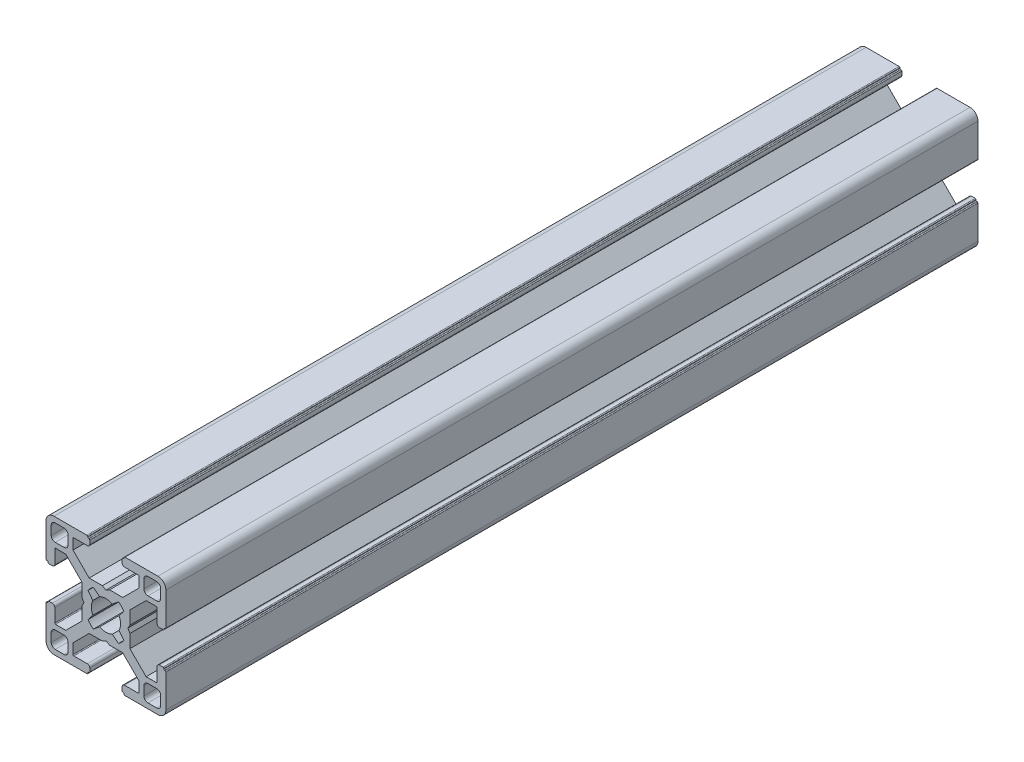
SolidWorks part; units mm, degrees
material "6061 Alloy"
ref_plane "Front" through (0, 0, 0) normal (0, 0, 1) x (1, 0, 0)
ref_plane "Top" through (0, 0, 0) normal (0, 1, 0) x (1, 0, 0)
ref_plane "Right" through (0, 0, 0) normal (1, 0, 0) x (0, 0, -1)
sketch "Sketch1" plane through (0, 0, 0) normal (0, 0, 1) x (1, 0, 0)
  line L0 (13.7, 12.7) -> (13.7, 10.5)
  line L1 (10.5, 9.5) -> (12.7, 9.5)
  line L2 (9.5, 12.7) -> (9.5, 10.5)
  line L3 (10.5, 13.7) -> (12.7, 13.7)
  line L4 (3.1359, 4.5184) -> (1.6001, 3.2806)
  line L5 (3.2806, 1.6001) -> (4.5053, 3.1547)
  line L6 (6.0045, 0.9) -> (5.4849, 0)
  line L7 (6.0045, 4.2045) -> (6.0045, 0.9)
  line L8 (0, -5.4849) -> (0.9, -6)
  line L9 (0.9, -6) -> (4.2045, -6)
  line L10 (4.2045, -6) -> (8.25, -10.05)
  line L11 (8.25, -10.05) -> (8.25, -12.6)
  line L12 (4.65, -12.8) -> (8.05, -12.8)
  line L13 (4.05, -14.3) -> (4.05, -13.4)
  line L14 (4.25, -14.5) -> (4.35, -14.5)
  line L15 (4.55, -14.8) -> (4.55, -14.7)
  line L16 (4.75, -15) -> (13, -15)
  line L17 (15, -13) -> (15, -4.75)
  line L18 (14.7, -4.55) -> (14.8, -4.55)
  line L19 (14.5, -4.35) -> (14.5, -4.25)
  line L20 (13.4, -4.05) -> (14.3, -4.05)
  line L21 (12.8, -8.05) -> (12.8, -4.65)
  line L22 (12.6, -8.25) -> (10.05, -8.25)
  line L23 (10.05, -8.25) -> (6.0045, -4.2045)
  line L24 (6.0045, -4.2045) -> (6.0045, -0.9)
  line L25 (6.0045, -0.9) -> (5.4849, 0)
  line L26 (10.05, 8.25) -> (6.0045, 4.2045)
  line L27 (12.6, 8.25) -> (10.05, 8.25)
  line L28 (12.8, 8.05) -> (12.8, 4.65)
  line L29 (13.4, 4.05) -> (14.3, 4.05)
  line L30 (14.5, 4.35) -> (14.5, 4.25)
  line L31 (14.7, 4.55) -> (14.8, 4.55)
  line L32 (15, 13) -> (15, 4.75)
  line L33 (4.75, 15) -> (13, 15)
  line L34 (4.55, 14.8) -> (4.55, 14.7)
  line L35 (4.25, 14.5) -> (4.35, 14.5)
  line L36 (4.05, 14.3) -> (4.05, 13.4)
  line L37 (4.65, 12.8) -> (8.05, 12.8)
  line L38 (8.25, 10.05) -> (8.25, 12.6)
  line L39 (4.2045, 6) -> (8.25, 10.05)
  line L40 (0.9, 6) -> (4.2045, 6)
  line L41 (0, 5.4849) -> (0.9, 6)
  line L42 (-13.7, -12.7) -> (-13.7, -10.5)
  line L43 (-10.5, -9.5) -> (-12.7, -9.5)
  line L44 (-9.5, -12.7) -> (-9.5, -10.5)
  line L45 (-10.5, -13.7) -> (-12.7, -13.7)
  line L46 (-3.1359, -4.5184) -> (-1.6001, -3.2806)
  line L47 (-3.2806, -1.6001) -> (-4.5053, -3.1547)
  line L48 (0, 5.4849) -> (-0.9, 6)
  line L49 (-0.9, 6) -> (-4.2045, 6)
  line L50 (-4.2045, 6) -> (-8.25, 10.05)
  line L51 (-8.25, 10.05) -> (-8.25, 12.6)
  line L52 (-4.65, 12.8) -> (-8.05, 12.8)
  line L53 (-4.05, 14.3) -> (-4.05, 13.4)
  line L54 (-4.25, 14.5) -> (-4.35, 14.5)
  line L55 (-4.55, 14.8) -> (-4.55, 14.7)
  line L56 (-4.75, 15) -> (-13, 15)
  line L57 (-15, 13) -> (-15, 4.75)
  line L58 (-14.7, 4.55) -> (-14.8, 4.55)
  line L59 (-14.5, 4.35) -> (-14.5, 4.25)
  line L60 (-13.4, 4.05) -> (-14.3, 4.05)
  line L61 (-12.8, 8.05) -> (-12.8, 4.65)
  line L62 (-12.6, 8.25) -> (-10.05, 8.25)
  line L63 (-10.05, 8.25) -> (-6.0045, 4.2045)
  line L64 (-6.0045, -0.9) -> (-5.4849, 0)
  line L65 (-6.0045, -4.2045) -> (-6.0045, -0.9)
  line L66 (-10.05, -8.25) -> (-6.0045, -4.2045)
  line L67 (-12.6, -8.25) -> (-10.05, -8.25)
  line L68 (-12.8, -8.05) -> (-12.8, -4.65)
  line L69 (-13.4, -4.05) -> (-14.3, -4.05)
  line L70 (-14.5, -4.35) -> (-14.5, -4.25)
  line L71 (-14.7, -4.55) -> (-14.8, -4.55)
  line L72 (-15, -13) -> (-15, -4.75)
  line L73 (-4.75, -15) -> (-13, -15)
  line L74 (-4.55, -14.8) -> (-4.55, -14.7)
  line L75 (-4.25, -14.5) -> (-4.35, -14.5)
  line L76 (-4.05, -14.3) -> (-4.05, -13.4)
  line L77 (3.2806, -1.6001) -> (4.5053, -3.1547)
  line L78 (3.1359, -4.5184) -> (1.6001, -3.2806)
  line L79 (-4.65, -12.8) -> (-8.05, -12.8)
  line L80 (-8.25, -10.05) -> (-8.25, -12.6)
  line L81 (-4.2045, -6) -> (-8.25, -10.05)
  line L82 (-0.9, -6) -> (-4.2045, -6)
  line L83 (0, -5.4849) -> (-0.9, -6)
  line L84 (10.5, -13.7) -> (12.7, -13.7)
  line L85 (9.5, -12.7) -> (9.5, -10.5)
  line L86 (10.5, -9.5) -> (12.7, -9.5)
  line L87 (13.7, -12.7) -> (13.7, -10.5)
  line L88 (-6.0045, 4.2045) -> (-6.0045, 0.9)
  line L89 (-6.0045, 0.9) -> (-5.4849, 0)
  line L90 (-3.2806, 1.6001) -> (-4.5053, 3.1547)
  line L91 (-3.1359, 4.5184) -> (-1.6001, 3.2806)
  line L92 (-10.5, 13.7) -> (-12.7, 13.7)
  line L93 (-9.5, 12.7) -> (-9.5, 10.5)
  line L94 (-10.5, 9.5) -> (-12.7, 9.5)
  line L95 (-13.7, 12.7) -> (-13.7, 10.5)
  line L96 (-23.4857, 0) -> (20.9308, 0) construction
  line L97 (0, 17.9563) -> (0, -17.361) construction
  arc A0 (13.7, 12.7) -> (12.7, 13.7) centre (12.7, 12.7) ccw
  arc A1 (12.7, 9.5) -> (13.7, 10.5) centre (12.7, 10.5) ccw
  arc A2 (9.5, 10.5) -> (10.5, 9.5) centre (10.5, 10.5) ccw
  arc A3 (10.5, 13.7) -> (9.5, 12.7) centre (10.5, 12.7) ccw
  arc A4 (1.6001, 3.2806) -> (-1.6001, 3.2806) centre (0, 0) ccw
  arc A5 (8.25, -12.6) -> (8.05, -12.8) centre (8.05, -12.6) cw
  arc A6 (4.65, -12.8) -> (4.05, -13.4) centre (4.65, -13.4) ccw
  arc A7 (4.05, -14.3) -> (4.25, -14.5) centre (4.25, -14.3) ccw
  arc A8 (4.35, -14.5) -> (4.55, -14.7) centre (4.35, -14.7) cw
  arc A9 (4.55, -14.8) -> (4.75, -15) centre (4.75, -14.8) ccw
  arc A10 (13, -15) -> (15, -13) centre (13, -13) ccw
  arc A11 (15, -4.75) -> (14.8, -4.55) centre (14.8, -4.75) ccw
  arc A12 (14.7, -4.55) -> (14.5, -4.35) centre (14.7, -4.35) cw
  arc A13 (14.5, -4.25) -> (14.3, -4.05) centre (14.3, -4.25) ccw
  arc A14 (13.4, -4.05) -> (12.8, -4.65) centre (13.4, -4.65) ccw
  arc A15 (12.8, -8.05) -> (12.6, -8.25) centre (12.6, -8.05) cw
  arc A16 (4.5053, 3.1547) -> (3.1359, 4.5184) centre (0, 0) ccw
  arc A17 (12.8, 8.05) -> (12.6, 8.25) centre (12.6, 8.05) ccw
  arc A18 (13.4, 4.05) -> (12.8, 4.65) centre (13.4, 4.65) cw
  arc A19 (14.5, 4.25) -> (14.3, 4.05) centre (14.3, 4.25) cw
  arc A20 (14.7, 4.55) -> (14.5, 4.35) centre (14.7, 4.35) ccw
  arc A21 (15, 4.75) -> (14.8, 4.55) centre (14.8, 4.75) cw
  arc A22 (13, 15) -> (15, 13) centre (13, 13) cw
  arc A23 (4.55, 14.8) -> (4.75, 15) centre (4.75, 14.8) cw
  arc A24 (4.35, 14.5) -> (4.55, 14.7) centre (4.35, 14.7) ccw
  arc A25 (4.05, 14.3) -> (4.25, 14.5) centre (4.25, 14.3) cw
  arc A26 (4.65, 12.8) -> (4.05, 13.4) centre (4.65, 13.4) cw
  arc A27 (8.25, 12.6) -> (8.05, 12.8) centre (8.05, 12.6) ccw
  arc A28 (-13.7, -12.7) -> (-12.7, -13.7) centre (-12.7, -12.7) ccw
  arc A29 (-12.7, -9.5) -> (-13.7, -10.5) centre (-12.7, -10.5) ccw
  arc A30 (-9.5, -10.5) -> (-10.5, -9.5) centre (-10.5, -10.5) ccw
  arc A31 (-10.5, -13.7) -> (-9.5, -12.7) centre (-10.5, -12.7) ccw
  arc A32 (-4.5053, -3.1547) -> (-3.1359, -4.5184) centre (0, 0) ccw
  arc A33 (-3.2806, 1.6001) -> (-3.2806, -1.6001) centre (0, 0) ccw
  arc A34 (-8.25, 12.6) -> (-8.05, 12.8) centre (-8.05, 12.6) cw
  arc A35 (-4.65, 12.8) -> (-4.05, 13.4) centre (-4.65, 13.4) ccw
  arc A36 (-4.05, 14.3) -> (-4.25, 14.5) centre (-4.25, 14.3) ccw
  arc A37 (-4.35, 14.5) -> (-4.55, 14.7) centre (-4.35, 14.7) cw
  arc A38 (-4.55, 14.8) -> (-4.75, 15) centre (-4.75, 14.8) ccw
  arc A39 (-13, 15) -> (-15, 13) centre (-13, 13) ccw
  arc A40 (-15, 4.75) -> (-14.8, 4.55) centre (-14.8, 4.75) ccw
  arc A41 (-14.7, 4.55) -> (-14.5, 4.35) centre (-14.7, 4.35) cw
  arc A42 (-14.5, 4.25) -> (-14.3, 4.05) centre (-14.3, 4.25) ccw
  arc A43 (-13.4, 4.05) -> (-12.8, 4.65) centre (-13.4, 4.65) ccw
  arc A44 (-12.8, 8.05) -> (-12.6, 8.25) centre (-12.6, 8.05) cw
  arc A45 (-4.5053, 3.1547) -> (-3.1359, 4.5184) centre (0, 0) cw
  arc A46 (-12.8, -8.05) -> (-12.6, -8.25) centre (-12.6, -8.05) ccw
  arc A47 (-13.4, -4.05) -> (-12.8, -4.65) centre (-13.4, -4.65) cw
  arc A48 (-14.5, -4.25) -> (-14.3, -4.05) centre (-14.3, -4.25) cw
  arc A49 (3.2806, 1.6001) -> (3.2806, -1.6001) centre (0, 0) cw
  arc A50 (4.5053, -3.1547) -> (3.1359, -4.5184) centre (0, 0) cw
  arc A51 (1.6001, -3.2806) -> (-1.6001, -3.2806) centre (0, 0) cw
  arc A52 (-14.7, -4.55) -> (-14.5, -4.35) centre (-14.7, -4.35) ccw
  arc A53 (-15, -4.75) -> (-14.8, -4.55) centre (-14.8, -4.75) cw
  arc A54 (-13, -15) -> (-15, -13) centre (-13, -13) cw
  arc A55 (-4.55, -14.8) -> (-4.75, -15) centre (-4.75, -14.8) cw
  arc A56 (10.5, -13.7) -> (9.5, -12.7) centre (10.5, -12.7) cw
  arc A57 (9.5, -10.5) -> (10.5, -9.5) centre (10.5, -10.5) cw
  arc A58 (12.7, -9.5) -> (13.7, -10.5) centre (12.7, -10.5) cw
  arc A59 (13.7, -12.7) -> (12.7, -13.7) centre (12.7, -12.7) cw
  arc A60 (-4.35, -14.5) -> (-4.55, -14.7) centre (-4.35, -14.7) ccw
  arc A61 (-4.05, -14.3) -> (-4.25, -14.5) centre (-4.25, -14.3) cw
  arc A62 (-4.65, -12.8) -> (-4.05, -13.4) centre (-4.65, -13.4) cw
  arc A63 (-8.25, -12.6) -> (-8.05, -12.8) centre (-8.05, -12.6) ccw
  arc A64 (-10.5, 13.7) -> (-9.5, 12.7) centre (-10.5, 12.7) cw
  arc A65 (-9.5, 10.5) -> (-10.5, 9.5) centre (-10.5, 10.5) cw
  arc A66 (-12.7, 9.5) -> (-13.7, 10.5) centre (-12.7, 10.5) cw
  arc A67 (-13.7, 12.7) -> (-12.7, 13.7) centre (-12.7, 12.7) cw
  point P81 (15, 15)
  point P82 (0, 15)
  point P203 (0, -15)
  point P204 (15, -15)
  point P206 (0, 0)
  point P207 (15, 0)
  point P219 (-15, 0)
  point P220 (-15, -15)
  point P221 (-15, 15)
  dimension "D6" = 7.3
  dimension "D7" = 11
  dimension "D1" = 30
  dimension "D2" = 15
  dimension "D3" = 30
  dimension "D4" = 8.1
  dimension "D5" = 9
  dimension "D8" = 8.1
extrude "Boss-Extrude1" add sketch "Sketch1" along normal blind 203.2
